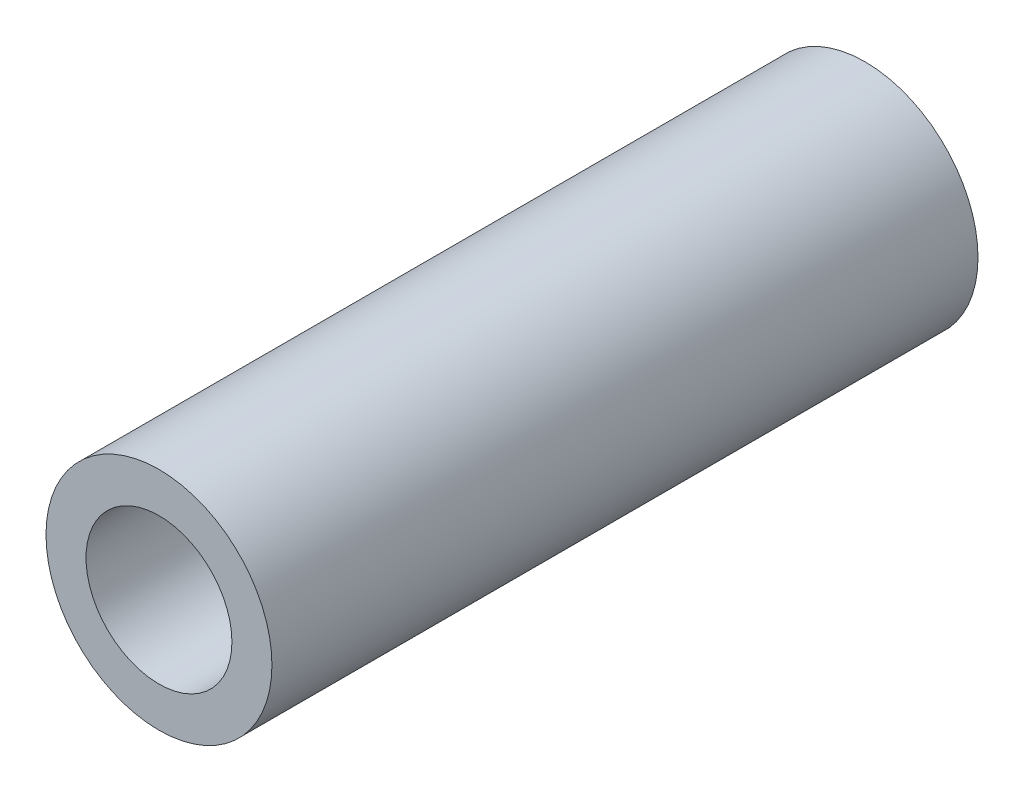
SolidWorks part; units mm, degrees
ref_plane "Front Plane" through (0, 0, 0) normal (0, 0, 1) x (1, 0, 0)
ref_plane "Top Plane" through (0, 0, 0) normal (0, 1, 0) x (1, 0, 0)
ref_plane "Right Plane" through (0, 0, 0) normal (1, 0, 0) x (0, 0, -1)
sketch "Sketch1" plane through (0, 0, 0) normal (0, 0, 1) x (1, 0, 0)
  circle A0 centre (-33.893, 10.6703) radius 2.4
  circle A1 centre (-33.893, 10.6703) radius 1.55
extrude "Boss-Extrude1" add sketch "Sketch1" along normal blind 15
